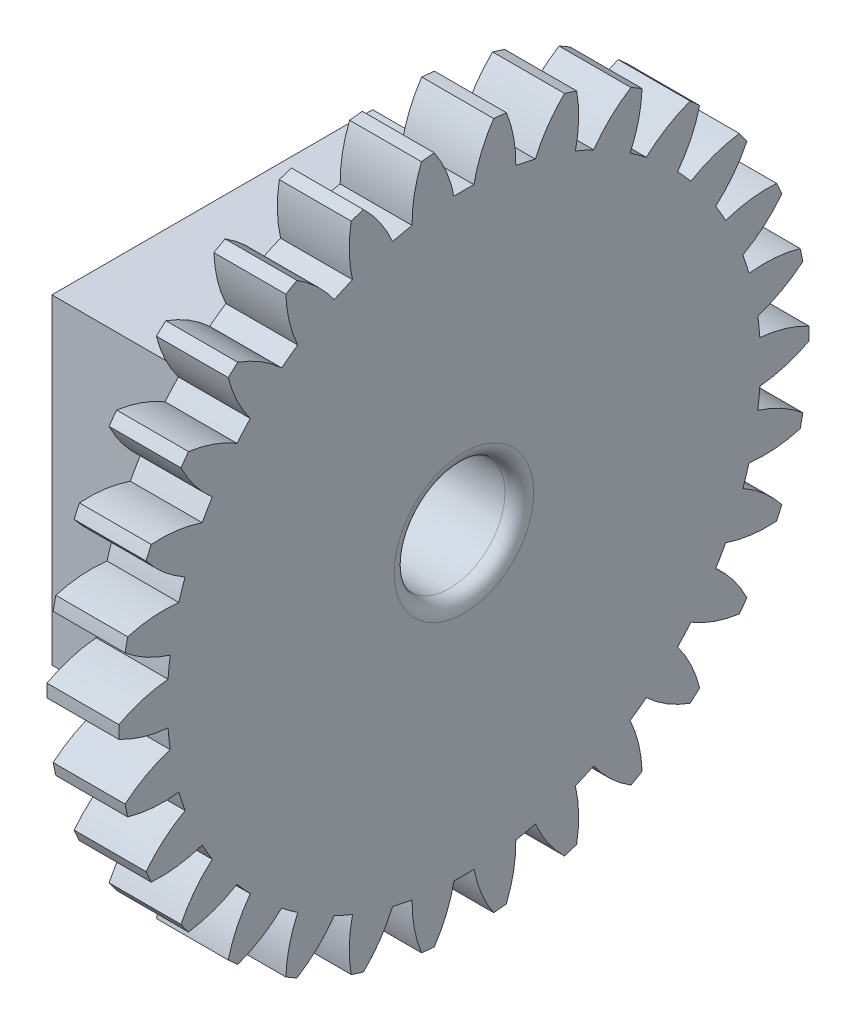
SolidWorks part; units mm, degrees
ref_plane "Plane1" through (0, 0, 0) normal (0, 0, 1) x (1, 0, 0)
ref_plane "Plane2" through (0, 0, 0) normal (0, 1, 0) x (1, 0, 0)
ref_plane "Plane3" through (0, 0, 0) normal (1, 0, 0) x (0, 0, -1)
other "Configuration Table"
sketch "HoldingSke" plane through (0, 0, 0) normal (0, 1, 0) x (1, 0, 0)
  line L0 (0, 0) -> (0.2887, -0.1667)
  line L1 (-15, 0) -> (100, 0) construction
  line L2 (0, 0) -> (-2.1039, 2.3779)
  line L3 (0, 0) -> (-11.863, 4.5341)
  line L4 (0, 0) -> (7.479, 4.318)
  line L5 (0, 0) -> (-46.8476, -17.4728)
  line L6 (0, 0) -> (-8.2896, -5.593)
  line L7 (-2.1039, 2.3779) -> (8.6586, 51.2059)
  line L8 (-76.2, 54.61) -> (-74.4, 54.61)
  line L9 (-71.009, 38.7566) -> (-53.1078, 45.2721)
  line L10 (-76.2, 71.12) -> (104.1128, 71.12)
  line L11 (0, 0) -> (-10, 0)
  line L12 (-76.2, 101.6) -> (-76.093, 101.6)
  line L13 (24.9733, 27.94) -> (52.9518, 28.4284)
  line L14 (24.9733, 27.94) -> (24.9743, 27.94)
  line L15 (24.9733, 27.94) -> (100.4006, 29.5858)
  line L16 (-63.627, -3) -> (-12.827, -3)
  circle A0 centre (0, 0) radius 5
  circle A1 centre (0, 0) radius 37.5
  circle A2 centre (0, 0) radius 37.5
  circle A3 centre (0, 0) radius 5
  dimension "MHD" = 75
  dimension "Hub_dia" = 75
  dimension "Bore" = 10
  dimension "MBD" = 10
  dimension "Num_teeth" = 30
  dimension "Pitch" = 0.3333
  dimension "Overall_len" = 50
  dimension "Show_teeth" = 30
  dimension "Thickness" = 10
  dimension "OAL" = 50.0001
  dimension "T_dim" = 1.8
  dimension "Ap" = 20
  dimension "H" = 19.05
  dimension "Pitch_radius" = 180.3128
  dimension "Width" = 10
  dimension "Backlash" = 0.107
  dimension "Addendum_fac" = 1
  dimension "Dedendum_fac" = 1.25
  dimension "Clearance_fac" = 0.25
  dimension "Dedendum_add" = 0.001
  dimension "Module" = 3
sketch "BasProSke" plane through (0, 0, 0) normal (0, 1, 0) x (1, 0, 0)
  line L0 (-10, 0) -> (60, 0) construction
  line L1 (0, 0) -> (0, 48)
  line L2 (0, 0) -> (10, 0)
  line L3 (10, 0) -> (10, 48)
  line L4 (10, 48) -> (0, 48)
  dimension "Thickness" = 10
  dimension "Diameter" = 96
revolve "Base-Revolve" add sketch "BasProSke" angle 360 about L0
sketch "TooCutSke" plane through (0, 0, 0) normal (1, 0, 0) x (0, 0, -1)
  line L1 (0, 0) -> (0, 107) construction
  line L2 (0, 0) -> (-2.5423, 44.9281) construction
  line L3 (0, 0) -> (-9.3966, 89.403) construction
  line L4 (-2.5423, 44.9281) -> (-4.6983, 44.7015) construction
  arc A0 (1.3884, 41.2256) -> (-1.3884, 41.2256) centre (0, 0) ccw
  arc A1 (4.1466, 47.8461) -> (-4.1466, 47.8461) centre (0, 0) ccw
  circle A2 centre (0, 0) radius 45 construction
  circle A3 centre (0, 0) radius 42.2862 construction
  arc A4 (-1.3884, 41.2256) -> (-4.1466, 47.8461) centre (-19.05, 37.752) ccw
  arc A5 (4.1466, 47.8461) -> (1.3884, 41.2256) centre (19.05, 37.752) ccw
  dimension "Root_dia" = 82.498
  dimension "Overcut_dia" = 96.0508
  dimension "Pitch_dia" = 90
  dimension "Base_dia" = 84.5723
  dimension "Flank_rad" = 18
  dimension "Half_ang" = 6
  dimension "Half_CT" = 2.1679
extrude "ToothCut" cut sketch "TooCutSke" along normal through all
fillet "Breaks" [suppressed] radius 0.06
fillet "RootFillets" [suppressed] radius 0.751
pattern_circular "TeethCuts" count 30 every 12 about axis through (-10, 0, 0) along (1, 0, 0) of "ToothCut", "RootFillets", "Breaks"
sketch "HubNeaOneSke" plane through (0, 0, 0) normal (-1, 0, 0) x (0, 0, 1)
  circle A0 centre (0, 0) radius 37.5
  dimension "Diameter" = 75
extrude "HubNearOne" [suppressed] add sketch "HubNeaOneSke" along normal blind 40.0001
sketch "HubNeaBotSke" plane through (0, 0, 0) normal (-1, 0, 0) x (0, 0, 1)
  circle A0 centre (0, 0) radius 37.5
  dimension "Diameter" = 75
extrude "HubNearBoth" [suppressed] add sketch "HubNeaBotSke" along normal blind 20
ref_plane "FarPln" through (10, 0, 0) normal (1, 0, 0) x (0, 0, -1)
sketch "HubFarSke" plane through (10, 0, 0) normal (1, 0, 0) x (0, 0, -1)
  circle A0 centre (0, 0) radius 37.5
  dimension "Diameter" = 75
extrude "HubFar" [suppressed] add sketch "HubFarSke" along normal blind 20
sketch "BorSke" plane through (0, 0, 0) normal (1, 0, 0) x (0, 0, -1)
  circle A0 centre (0, 0) radius 5
  dimension "Diameter" = 10
extrude "Bore" cut sketch "BorSke" along normal mid plane 100.0001
sketch "KeySke" plane through (0, 0, 0) normal (1, 0, 0) x (0, 0, -1)
  line L0 (-2, 0) -> (-2, 6.8)
  line L1 (-2, 6.8) -> (2, 6.8)
  line L2 (2, 6.8) -> (2, 0)
  line L3 (0, 0) -> (0, 34) construction
  line L4 (-2, 0) -> (2, 0)
  dimension "Offset" = 6.8
  dimension "Width" = 4
extrude "Keyway" [suppressed] cut sketch "KeySke" along normal mid plane 100.0001
pattern_circular "Keyway2" [suppressed] count 2 every 90 about axis through (-10, 0, 0) along (1, 0, 0)
sketch "Sketch1" plane through (10, 0, 0) normal (1, 0, 0) x (0, 0, -1)
  circle A0 centre (0, 0) radius 7.7
  dimension "D1" = 15.4
sketch "Sketch2" plane through (0, 0, 0) normal (-1, 0, 0) x (0, 0, 1)
  line L0 (-22.3, 22.3) -> (22.3, -22.3) construction
  line L1 (-22.3, 22.3) -> (22.3, 22.3)
  line L2 (-22.3, 22.3) -> (-22.3, -22.3)
  line L3 (-22.3, -22.3) -> (22.3, -22.3)
  line L4 (22.3, 22.3) -> (22.3, -22.3)
  dimension "D1" = 44.6
extrude "Boss-Extrude1" add sketch "Sketch2" along normal blind 60
extrude "Cut-Extrude1" cut sketch "Sketch1" against normal up to next
sketch "Sketch3" plane through (0, 22.3, 0) normal (0, 1, 0) x (1, 0, 0)
  line L0 (-60, -22.3) -> (0, -22.3) construction
  line L1 (-60, 22.3) -> (-25, 22.3)
  line L2 (-60, 22.3) -> (-60, -22.3)
  line L3 (-60, -22.3) -> (-25, -22.3)
  line L4 (-25, 22.3) -> (-25, -22.3)
  dimension "D1" = 35
extrude "Cut-Extrude2" cut sketch "Sketch3" against normal up to next
fillet "Fillet1" radius 2 2 edges at (10, 0, -7.7) (-25, 0, -7.7)
equation "' \"Module@HoldingSke\" = 6.35"
equation "' \"Num_teeth@HoldingSke\" = 12"
equation "' \"Ap@HoldingSke\" =  20"
equation "' \"Ap@HoldingSke\" = 20"
equation "' \"Width@HoldingSke\" = 0.5 * 25.4"
equation "' \"Hub_dia@HoldingSke\"= 1 * 25.4"
equation "' \"Hub_dia@HoldingSke\" = 1 * 25.4"
equation "' \"Overall_len@HoldingSke\" = 1.0 * 25.4"
equation "' \"Bore@HoldingSke\" = 0.75 * 25.4"
equation "' \"T_dim@HoldingSke\" = 0.1 * 25.4"
equation "' \"Width@KeySke\" = 0.25 * 25.4"
equation "' \"Show_teeth@HoldingSke\" = 13"
equation "' \"Backlash@HoldingSke\" = 0.009 * 25.4"
equation "' \"Addendum_fac@HoldingSke\" = 1.0"
equation "' \"Dedendum_fac@HoldingSke\" = 1.25"
equation "' \"Dedendum_add@HoldingSke\" = 0.00005 * 25.4"
equation "' \"Clearance_fac@HoldingSke\" = 0.25"
equation "\"Pitch@HoldingSke\" = 1 / \"Module@HoldingSke\""
equation "\"Overcut_dia@TooCutSke\" = (\"Num_teeth@HoldingSke\" + 2 * \"Addendum_fac@HoldingSke\") / \"Pitch@HoldingSke\" + 0.002 * 25.4"
equation "\"Pitch_dia@TooCutSke\" = \"Num_teeth@HoldingSke\" / \"Pitch@HoldingSke\""
equation "\"Base_dia@TooCutSke\" = \"Num_teeth@HoldingSke\" / \"Pitch@HoldingSke\" * cos((\"Ap@HoldingSke\"  * 3.14159265 / 180))"
equation "\"Root_dia@TooCutSke\" = (\"Num_teeth@HoldingSke\" + 2) / \"Pitch@HoldingSke\" - 2 * (\"Addendum_fac@HoldingSke\" + \"Dedendum_fac@HoldingSke\") / \"Pitch@HoldingSke\" - \"Dedendum_add@HoldingSke\" * 2"
equation "\"Half_ang@TooCutSke\" = 180 / \"Num_teeth@HoldingSke\""
equation "\"Half_CT@TooCutSke\" = \"Num_teeth@HoldingSke\" / \"Pitch@HoldingSke\" * sin((3.14159265 / 2 / \"Num_teeth@HoldingSke\")) / 2 - 7 * \"Backlash@HoldingSke\" / 4"
equation "\"Flank_rad@TooCutSke\" = \"Num_teeth@HoldingSke\" / \"Pitch@HoldingSke\" / 5"
equation "\"Radius@RootFillets\" = \"Clearance_fac@HoldingSke\" / \"Pitch@HoldingSke\" + \"Dedendum_add@HoldingSke\""
equation "\"Break_rad@Breaks\" = 0.02 / \"Pitch@HoldingSke\""
equation "\"Thickness@HoldingSke\" = \"Width@HoldingSke\""
equation "\"OAL@HoldingSke\" = \"Thickness@HoldingSke\""
equation "\"MHD@HoldingSke\" = (\"Num_teeth@HoldingSke\" + 2) / \"Pitch@HoldingSke\" - 2 * (\"Addendum_fac@HoldingSke\" + \"Dedendum_fac@HoldingSke\")  / \"Pitch@HoldingSke\" - \"Dedendum_add@HoldingSke\" * 2"
equation "\"MBD@HoldingSke\" = (\"Num_teeth@HoldingSke\" + 2) / \"Pitch@HoldingSke\" - 2 * (\"Addendum_fac@HoldingSke\" + \"Dedendum_fac@HoldingSke\")  / \"Pitch@HoldingSke\" - \"Dedendum_add@HoldingSke\" * 2 - 0.002 * 25.4"
equation "\"MHD@HoldingSke\" = ((sgn( \"MHD@HoldingSke\" - \"Hub_dia@HoldingSke\" )-1)*( \"MHD@HoldingSke\" - \"Hub_dia@HoldingSke\" ))/-2+ \"Hub_dia@HoldingSke\""
equation "\"MBD@HoldingSke\" = ((sgn( \"MBD@HoldingSke\" - \"Bore@HoldingSke\" )-1)*( \"MBD@HoldingSke\" - \"Bore@HoldingSke\" ))/-2+ \"Bore@HoldingSke\""
equation "\"OAL@HoldingSke\" = ((sgn( \"OAL@HoldingSke\" - \"Overall_len@HoldingSke\" )+1)*( \"OAL@HoldingSke\" - \"Overall_len@HoldingSke\" ))/2 + \"Overall_len@HoldingSke\" + 0.000002 * 25.4"
equation "\"Num_teeth@TeethCuts\" = int( \"Show_teeth@HoldingSke\" ) + 1"
equation "\"Num_teeth@TeethCuts\" = ((sgn( \"Num_teeth@TeethCuts\" - \"Num_teeth@HoldingSke\" )-1)*( \"Num_teeth@TeethCuts\" - \"Num_teeth@HoldingSke\" ))/-2+ \"Num_teeth@HoldingSke\""
equation "\"Num_teeth@TeethCuts\" = ((sgn( \"Num_teeth@TeethCuts\" - 2.0)+1)*( \"Num_teeth@TeethCuts\" - 2.0))/2 +2.0"
equation "\"Angle@TeethCuts\" = 360.0 / \"Num_teeth@HoldingSke\""
equation "\"Diameter@BasProSke\" = (\"Num_teeth@HoldingSke\" + 2 * \"Addendum_fac@HoldingSke\") / \"Pitch@HoldingSke\""
equation "\"Thickness@BasProSke\"  = \"Thickness@HoldingSke\""
equation "' \"Fillet_rad@BasProSke\" =  \"Thickness@HoldingSke\" * 0.05"
equation "' \"Fillet_rad@BasProSke\" = \"Thickness@HoldingSke\" * 0.05"
equation "\"MHD@HoldingSke\" = ((sgn( \"MHD@HoldingSke\" - \"Root_dia@TooCutSke\" )-1)*( \"MHD@HoldingSke\" - \"Root_dia@TooCutSke\" ))/-2+ \"Root_dia@TooCutSke\""
equation "\"Diameter@HubNeaOneSke\" = \"MHD@HoldingSke\""
equation "\"Length@HubNearOne\" = \"OAL@HoldingSke\" - \"Thickness@BasProSke\""
equation "\"Diameter@HubNeaBotSke\" = \"MHD@HoldingSke\""
equation "\"Length@HubNearBoth\" = ( \"OAL@HoldingSke\" - \"Thickness@BasProSke\" ) / 2.0"
equation "\"Thickness@FarPln\" = \"Thickness@BasProSke\""
equation "\"Diameter@HubFarSke\" = \"MHD@HoldingSke\""
equation "\"Length@HubFar\" = ( \"OAL@HoldingSke\" - \"Thickness@BasProSke\" ) / 2.0"
equation "\"Diameter@BorSke\" = \"MBD@HoldingSke\""
equation "\"D1@Bore\" = \"OAL@HoldingSke\" * 2.0"
equation "\"D1@Keyway\" = \"OAL@HoldingSke\" * 2.0"
equation "\"Offset@KeySke\" = \"T_dim@HoldingSke\" + \"MBD@HoldingSke\" / 2.0"
